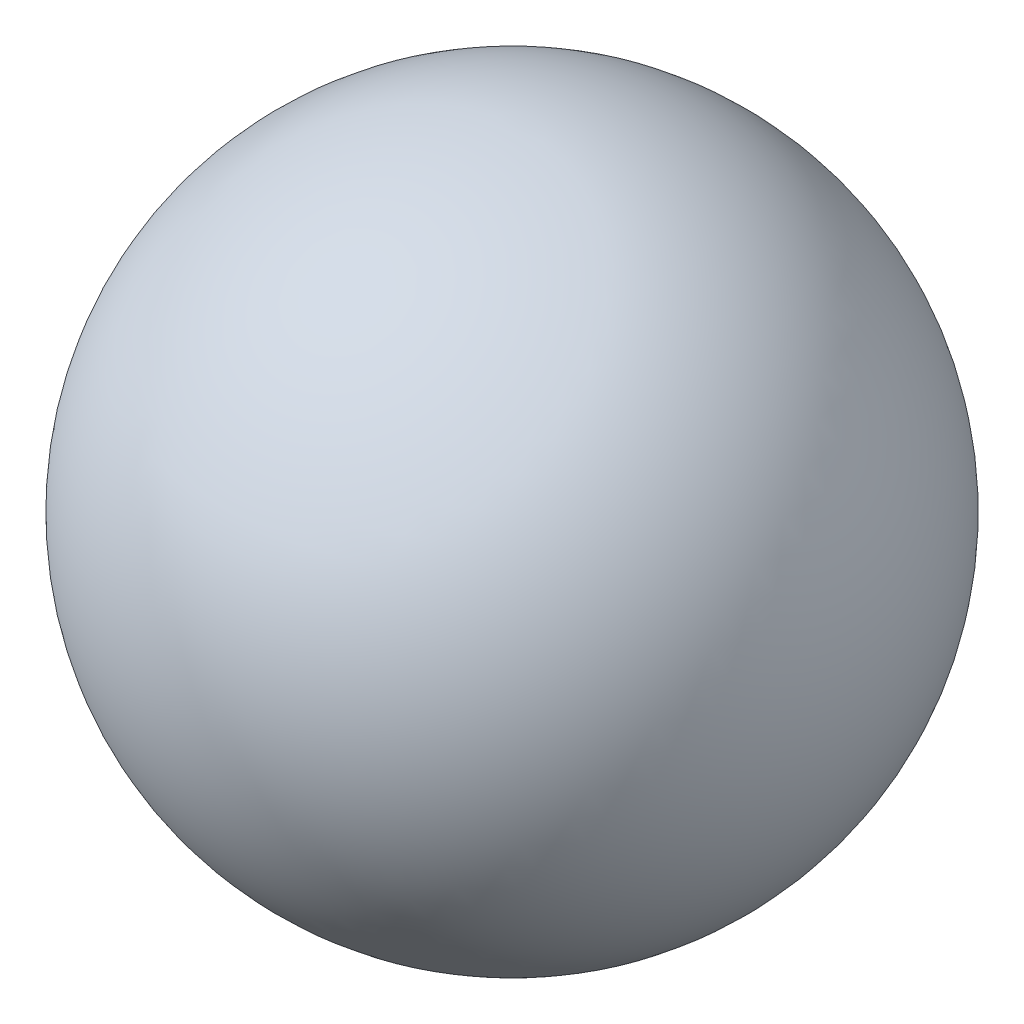
SolidWorks part; units mm, degrees
ref_plane "Plan de face" through (0, 0, 0) normal (0, 0, 1) x (1, 0, 0)
ref_plane "Plan de dessus" through (0, 0, 0) normal (0, 1, 0) x (1, 0, 0)
ref_plane "Plan de droite" through (0, 0, 0) normal (1, 0, 0) x (0, 0, -1)
sketch "Esquisse2" plane through (0, 0, 0) normal (0, 0, 1) x (1, 0, 0)
  line L0 (0, 30) -> (0, -30)
  arc A0 (0, 30) -> (0, -30) centre (0, 0) ccw
  dimension "D1" = 60
revolve "Révolution1" add sketch "Esquisse2" angle 360 about L0
